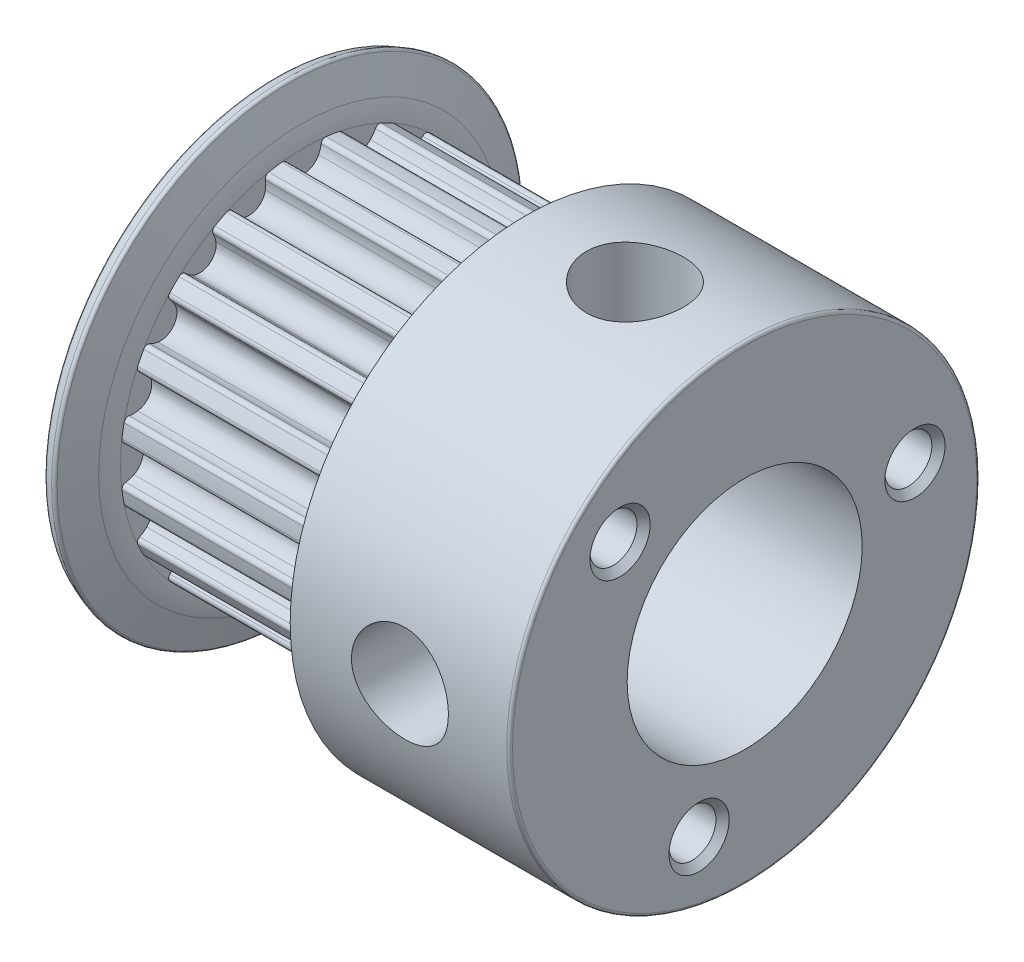
SolidWorks part; units mm, degrees
ref_plane "Front" through (0, 0, 0) normal (0, 0, 1) x (1, 0, 0)
ref_plane "Top" through (0, 0, 0) normal (0, 1, 0) x (1, 0, 0)
ref_plane "Right" through (0, 0, 0) normal (1, 0, 0) x (0, 0, -1)
sketch "Sketch1" plane through (0, 0, 0) normal (1, 0, 0) x (0, 0, -1)
  circle A0 centre (0, 0) radius 4
  circle A1 centre (0, 0) radius 6.2392
  dimension "D1" = 8
  dimension "D2" = 12.4784
extrude "Boss-Extrude1" add sketch "Sketch1" along normal mid plane 7
sketch "Sketch2" plane through (0, 0, 0) normal (1, 0, 0) x (0, 0, -1)
  line L0 (0, 0) -> (0, 6.2392) construction
  circle A0 centre (0, 0) radius 6.2392 construction
  arc A1 (0.7537, 6.1935) -> (-0.7537, 6.1935) centre (0, 0) ccw
  arc A2 (-0.7537, 6.1935) -> (-0.5874, 6.0683) centre (-0.7355, 6.0446) cw
  arc A3 (-0.5874, 6.0683) -> (-0.4989, 5.7882) centre (0.4, 6.2264) ccw
  arc A4 (-0.4989, 5.7882) -> (0.4989, 5.7882) centre (0, 6.0314) ccw
  arc A5 (0.7537, 6.1935) -> (0.5874, 6.0683) centre (0.7355, 6.0446) ccw
  arc A6 (0.5874, 6.0683) -> (0.4989, 5.7882) centre (-0.4, 6.2264) cw
  dimension "D1" = 0.15
  dimension "D2" = 1
  dimension "D3" = 0.555
  dimension "D4" = 0.4
extrude "Cut-Extrude1" cut sketch "Sketch2" against normal mid plane 7
pattern_circular "CirPattern1" count 20 over 360 about axis through (0, 0, 0) along (1, 0, 0) of "Cut-Extrude1"
sketch "Sketch3" plane through (0, 0, 0) normal (0, 0, 1) x (1, 0, 0)
  line L0 (0, 6.2392) -> (0, 0) construction
  line L1 (0, 0) -> (5.1043, 0) construction
  line L2 (-3.5, 4) -> (-3.5, 6.2392)
  line L3 (-3.614, 6.8748) -> (-4.0312, 8)
  line L4 (-4.0312, 8) -> (-4.5, 7.8262)
  line L5 (-4.5, 7.8262) -> (-4.0829, 6.701)
  line L7 (-4, 6.2392) -> (-4, 5)
  line L8 (-4, 5) -> (-4.25, 5)
  line L9 (-4.25, 5) -> (-4.25, 4.5)
  line L10 (-4.25, 4.5) -> (-4.5, 4.5)
  line L11 (-4.5, 4.5) -> (-4.5, 4)
  line L12 (-4.5, 4) -> (-3.5, 4)
  line L16 (4.5, 4.5) -> (4.5, 4)
  line L17 (4.25, 4.5) -> (4.5, 4.5)
  line L18 (4.25, 5) -> (4.25, 4.5)
  line L19 (4, 5) -> (4.25, 5)
  line L20 (4, 6.2392) -> (4, 5)
  line L21 (4.5, 7.8262) -> (4.0829, 6.701)
  line L22 (4.0312, 8) -> (4.5, 7.8262)
  line L23 (3.614, 6.8748) -> (4.0312, 8)
  line L24 (3.5, 4) -> (3.5, 6.2392)
  line L25 (4.5, 4) -> (3.5, 4)
  arc A0 (-3.5, 6.2392) -> (-3.614, 6.8748) centre (-5.3285, 6.2392) ccw
  arc A1 (-4.0829, 6.701) -> (-4, 6.2392) centre (-5.3285, 6.2392) cw
  arc A2 (4.0829, 6.701) -> (4, 6.2392) centre (5.3285, 6.2392) ccw
  arc A3 (3.5, 6.2392) -> (3.614, 6.8748) centre (5.3285, 6.2392) cw
  dimension "D1" = 9
  dimension "D2" = 16
  dimension "D3" = 0.5
  dimension "D4" = 1.2
  dimension "D5" = 1
  dimension "D6" = 10
revolve "Revolve1" add sketch "Sketch3" angle 360 about L1
sketch "Sketch4" plane through (0, 0, 0) normal (0, 0, 1) x (1, 0, 0)
  line L0 (0, 7.2927) -> (0, 0) construction
  line L1 (0, 0) -> (12.9063, 0) construction
  line L2 (4.0312, 8) -> (4.0312, 0) construction
  line L4 (0, 0) -> (5.1043, 0) construction
  line L5 (4.0312, 8) -> (11.5, 8)
  line L6 (11.5, 8) -> (11.5, 4)
  line L7 (11.5, 4) -> (3.8216, 4)
  line L8 (3.8216, 4) -> (4.0312, 8)
  line L9 (4.5, 4) -> (3.5, 4) construction
  line L10 (-4.5, 4.5) -> (-4.5, 4) construction
  dimension "D2" = 16
  dimension "D1" = 16
  dimension "D3" = 93
revolve "Revolve2" add sketch "Sketch4" angle 360 about L1
fillet "Fillet1" radius 0.1 6 edges at (-4, 0, 5) (-4.25, 0, 5) (-4.25, 0, 4.5) (11.5, 0, 8) (-4.0312, 0, 8) (-4.5, 0, 7.8262)
sketch "Sketch5" plane through (0, 0, 0) normal (0, 0, 1) x (1, 0, 0)
  line L0 (4.0312, 0) -> (11.5, 0) construction
  line L1 (4.0312, 8) -> (4.0312, 0) construction
  line L2 (11.5, 8) -> (11.5, 4) construction
hole_wizard "M4 Tapped Hole1" positions "Sketch7" profile "Sketch6" tap size "M4" standard "ISO"
sketch "Sketch7" plane through (0, 0, 0) normal (0, 0, 1) x (1, 0, 0)
  line L0 (4.0312, 0) -> (11.5, 0) construction
  point P0 (7.7656, 0)
sketch "Sketch6" plane through (7.7656, 0, 0) normal (1, 0, 0) x (0, 1, 0)
  line L0 (0, 0) -> (0, 8)
  line L1 (0, 8) -> (1.65, 8)
  line L2 (1.65, 8) -> (1.65, 0)
  line L5 (1.65, 0) -> (0, 0)
  line L11 (0, -6.35) -> (0, 107.95) construction
  dimension "Thru Tap Drill Dia." = 3.3
  dimension "Thru Tap Drill Depth" = 8
cosmetic thread "Hole Thread1" parameters "D2"=4
hole_wizard "M4 Tapped Hole2" positions "Sketch10" profile "Sketch9" tap size "M4" standard "ISO"
sketch "Sketch10" plane through (0, 0, 0) normal (0, 1, 0) x (1, 0, 0)
  point P0 (7.7656, 0)
sketch "Sketch9" plane through (7.7656, 0, 0) normal (1, 0, 0) x (0, 0, -1)
  line L0 (0, 0) -> (0, 8)
  line L1 (0, 8) -> (1.65, 8)
  line L2 (1.65, 8) -> (1.65, 0.375)
  line L3 (1.65, 0.375) -> (2.025, 0)
  line L5 (2.025, 0) -> (0, 0)
  line L6 (-1.65, 0.375) -> (-2.025, 0) construction
  line L11 (0, -6.35) -> (0, 107.95) construction
  dimension "Thru Tap Drill Dia." = 3.3
  dimension "Thru Tap Drill Depth" = 8
  dimension "Near C'Sink Dia." = 4.05
  dimension "Near C'Sink Angle" = 90
cosmetic thread "Hole Thread2" parameters "D2"=4
hole_wizard "M2 Tapped Hole1" positions "Sketch13" profile "Sketch12" tap size "M2" standard "ISO"
sketch "Sketch13" plane through (11.5, 0, 0) normal (1, 0, 0) x (0, 0, -1)
  line L0 (0, 0) -> (0, 6) construction
  line L2 (0, 0) -> (-4.2426, 4.2426) construction
  line L4 (-4.2426, 4.2426) -> (-1.5529, -5.7956) construction
  line L5 (-1.5529, -5.7956) -> (5.7956, 1.5529) construction
  line L6 (5.7956, 1.5529) -> (-4.2426, 4.2426) construction
  circle A0 centre (0, 0) radius 6 construction
  point P0 (-4.2426, 4.2426)
  point P2 (5.7956, 1.5529)
  point P4 (-1.5529, -5.7956)
  dimension "D2" = 12
  dimension "D1" = 45
sketch "Sketch12" plane through (11.5, 4.2426, 4.2426) normal (0, 1, 0) x (0, 0, -1)
  line L0 (0, 0) -> (0, 8.4807)
  line L1 (0, 8.4807) -> (0.8, 8)
  line L2 (0.8, 8) -> (0.8, 0.225)
  line L3 (0.8, 0.225) -> (1.025, 0)
  line L5 (1.025, 0) -> (0, 0)
  line L6 (-0.8, 0.225) -> (-1.025, 0) construction
  line L10 (0, 8.4807) -> (-0.8, 8) construction
  line L11 (0, -6.35) -> (0, 107.95) construction
  dimension "Tap Drill Dia." = 1.6
  dimension "Tap Drill Depth" = 8
  dimension "Near C'Sink Dia." = 2.05
  dimension "Near C'Sink Angle" = 90
  dimension "Drill Angle" = 118
cosmetic thread "Hole Thread3" parameters "D1"=6, "D2"=2
cosmetic thread "Hole Thread4" parameters "D1"=6, "D2"=2
cosmetic thread "Hole Thread5" parameters "D1"=6, "D2"=2
equation "\"Pitch\"= 2"
equation "\"Outside Fillet\"= .15"
equation "\"Side Radius\"= 1"
equation "\"Bottom Radius\"= .555"
equation "\"Tooth height\"= .75"
equation "\"Teeth_Count\"=20"
equation "\"Side radius offset\"= .4"
equation "\"Effective radius offset\"= 0.254"
equation "\"Belt width\"= 6"
equation "\"Pulley extra width\"= 1"
equation "\"Rim_Diameter\"=16"
equation "\"Rim_Width\"= 1"
equation "\"Pulley_Width\"= \"Belt width\" + \"Pulley extra width\" + 2 * \"Rim_Width\""
equation "\"Overall Width\"= 16"
equation "\"Fastening Diameter\"=16"
equation "\"D2@Sketch1\"=\"Pitch\"*\"Teeth_Count\"/pi - \"Effective radius offset\""
equation "\"D1@Boss-Extrude1\"=\"Belt width\"+\"Pulley extra width\""
equation "\"D1@Sketch2\"=\"Outside Fillet\""
equation "\"D2@Sketch2\"=\"Side Radius\""
equation "\"D3@Sketch2\"=\"Bottom Radius\""
equation "\"D4@Sketch2\"=\"Side radius offset\""
equation "\"D1@Cut-Extrude1\"=\"Belt width\"+\"Pulley extra width\""
equation "\"D1@CirPattern1\"=\"Teeth_Count\""
equation "\"D2@Sketch3\"=\"Rim_Diameter\""
equation "\"D1@Sketch4\"=\"Fastening Diameter\""
equation "\"D2@Sketch4\"=\"Overall Width\""
